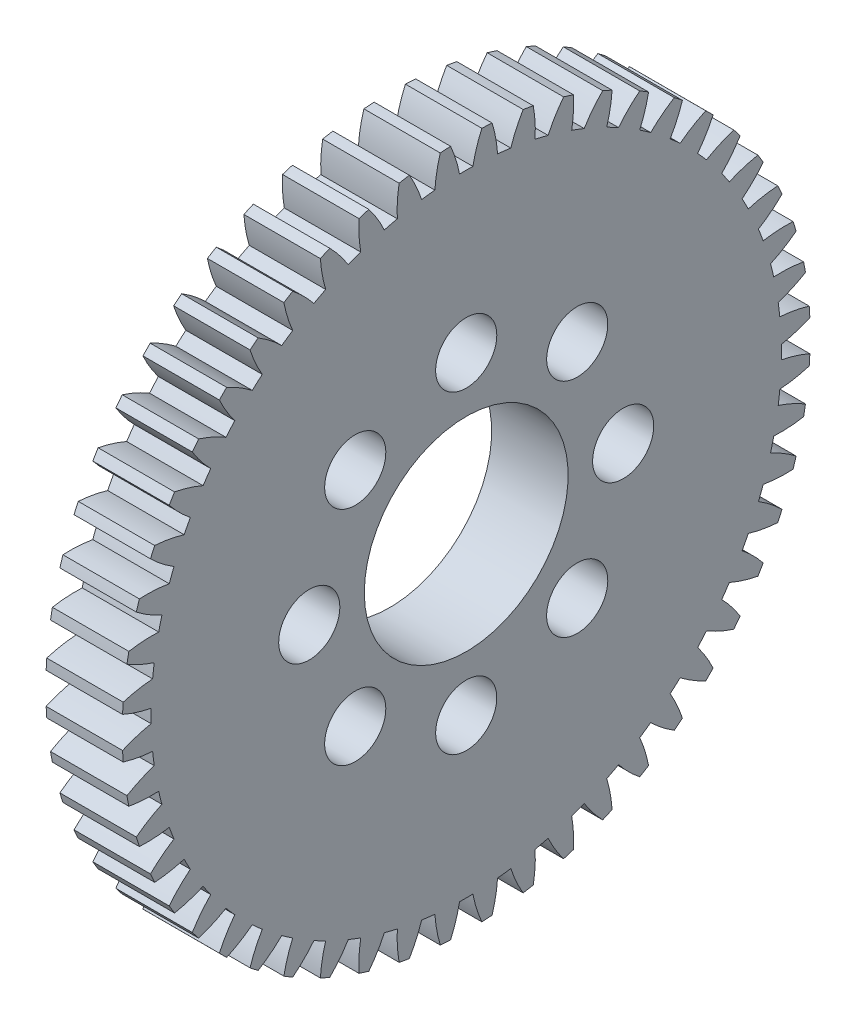
SolidWorks part; units mm, degrees
ref_plane "Front Plane" through (0, 0, 0) normal (0, 0, 1) x (1, 0, 0)
ref_plane "Top Plane" through (0, 0, 0) normal (0, 1, 0) x (1, 0, 0)
ref_plane "Right Plane" through (0, 0, 0) normal (1, 0, 0) x (0, 0, -1)
ref_plane "Plane1" through (-28.2082, 0, 0) normal (1, 0, 0) x (0, 0, -1)
sketch "Sketch1" plane through (-28.2082, 0, 0) normal (1, 0, 0) x (0, 0, -1)
  circle A0 centre (-12.9395, 1.6307) radius 6.35
  arc A1 (-34.3487, 2.6033) -> (-32.5693, 2.0468) centre (-31.0108, 10.1534) ccw
  arc A2 (-32.5693, 2.0468) -> (-32.5693, 1.2146) centre (-12.9395, 1.6307) ccw
  arc A3 (-32.5693, 1.2146) -> (-34.3487, 0.6581) centre (-31.0108, -6.892) ccw
  arc A4 (-34.3487, 0.6581) -> (-34.3098, 0.0156) centre (-12.9395, 1.6307) ccw
  arc A5 (-34.3098, 0.0156) -> (-32.4763, -0.3223) centre (-31.9063, 7.913) ccw
  arc A6 (-32.4763, -0.3223) -> (-32.376, -1.1485) centre (-12.9395, 1.6307) ccw
  arc A7 (-32.376, -1.1485) -> (-34.0753, -1.9154) centre (-29.8517, -9.0081) ccw
  arc A8 (-34.0753, -1.9154) -> (-33.9593, -2.5485) centre (-12.9395, 1.6307) ccw
  arc A9 (-33.9593, -2.5485) -> (-32.0985, -2.663) centre (-32.5252, 5.581) ccw
  arc A10 (-32.0985, -2.663) -> (-31.8993, -3.4711) centre (-12.9395, 1.6307) ccw
  arc A11 (-31.8993, -3.4711) -> (-33.4938, -4.4372) centre (-28.446, -10.9691) ccw
  arc A12 (-33.4938, -4.4372) -> (-33.3023, -5.0517) centre (-12.9395, 1.6307) ccw
  arc A13 (-33.3023, -5.0517) -> (-31.4412, -4.9411) centre (-32.8586, 3.1914) ccw
  arc A14 (-31.4412, -4.9411) -> (-31.1461, -5.7192) centre (-12.9395, 1.6307) ccw
  arc A15 (-31.1461, -5.7192) -> (-32.6125, -6.8705) centre (-26.8142, -12.7463) ccw
  arc A16 (-32.6125, -6.8705) -> (-32.3484, -7.4575) centre (-12.9395, 1.6307) ccw
  arc A17 (-32.3484, -7.4575) -> (-30.5142, -7.1233) centre (-32.9015, 0.779) ccw
  arc A18 (-30.5142, -7.1233) -> (-30.1274, -7.8602) centre (-12.9395, 1.6307) ccw
  arc A19 (-30.1274, -7.8602) -> (-31.4444, -9.1798) centre (-24.9801, -14.3139) ccw
  arc A20 (-31.4444, -9.1798) -> (-31.1114, -9.7307) centre (-12.9395, 1.6307) ccw
  arc A21 (-31.1114, -9.7307) -> (-29.3309, -9.1778) centre (-32.6533, -1.6209) ccw
  arc A22 (-29.3309, -9.1778) -> (-28.8581, -9.8628) centre (-12.9395, 1.6307) ccw
  arc A23 (-28.8581, -9.8628) -> (-30.0064, -11.3315) centre (-22.9704, -15.649) ccw
  arc A24 (-30.0064, -11.3315) -> (-29.6094, -11.8382) centre (-12.9395, 1.6307) ccw
  arc A25 (-29.6094, -11.8382) -> (-27.9085, -11.0748) centre (-32.1176, -3.9735) ccw
  arc A26 (-27.9085, -11.0748) -> (-27.3567, -11.6977) centre (-12.9395, 1.6307) ccw
  arc A27 (-27.3567, -11.6977) -> (-28.3195, -13.2942) centre (-20.8145, -16.7321) ccw
  arc A28 (-28.3195, -13.2942) -> (-27.8644, -13.7493) centre (-12.9395, 1.6307) ccw
  arc A29 (-27.8644, -13.7493) -> (-26.2679, -12.7865) centre (-31.3023, -6.2443) ccw
  arc A30 (-26.2679, -12.7865) -> (-25.645, -13.3384) centre (-12.9395, 1.6307) ccw
  arc A31 (-25.645, -13.3384) -> (-26.4084, -15.0393) centre (-18.5437, -17.5474) ccw
  arc A32 (-26.4084, -15.0393) -> (-25.9017, -15.4362) centre (-12.9395, 1.6307) ccw
  arc A33 (-25.9017, -15.4362) -> (-24.4329, -14.2879) centre (-30.2192, -8.4002) ccw
  arc A34 (-24.4329, -14.2879) -> (-23.748, -14.7607) centre (-12.9395, 1.6307) ccw
  arc A35 (-23.748, -14.7607) -> (-24.3009, -16.5412) centre (-16.1911, -18.0831) ccw
  arc A36 (-24.3009, -16.5412) -> (-23.75, -16.8742) centre (-12.9395, 1.6307) ccw
  arc A37 (-23.75, -16.8742) -> (-22.4304, -15.5572) centre (-28.8841, -10.4099) ccw
  arc A38 (-22.4304, -15.5572) -> (-21.6935, -15.944) centre (-12.9395, 1.6307) ccw
  arc A39 (-21.6935, -15.944) -> (-22.0276, -17.7782) centre (-13.7912, -18.3313) ccw
  arc A40 (-22.0276, -17.7782) -> (-21.4407, -18.0423) centre (-12.9395, 1.6307) ccw
  arc A41 (-21.4407, -18.0423) -> (-20.2894, -16.5759) centre (-27.3165, -12.2441) ccw
  arc A42 (-20.2894, -16.5759) -> (-19.5112, -16.871) centre (-12.9395, 1.6307) ccw
  arc A43 (-19.5112, -16.871) -> (-19.6219, -18.7321) centre (-11.3788, -18.2884) ccw
  arc A44 (-19.6219, -18.7321) -> (-19.0074, -18.9236) centre (-12.9395, 1.6307) ccw
  arc A45 (-19.0074, -18.9236) -> (-18.0412, -17.3291) centre (-25.5392, -13.8758) ccw
  arc A46 (-18.0412, -17.3291) -> (-17.2332, -17.5283) centre (-12.9395, 1.6307) ccw
  arc A47 (-17.2332, -17.5283) -> (-17.1187, -19.3891) centre (-8.9892, -17.9551) ccw
  arc A48 (-17.1187, -19.3891) -> (-16.4856, -19.5051) centre (-12.9395, 1.6307) ccw
  arc A49 (-16.4856, -19.5051) -> (-15.7187, -17.8058) centre (-23.5783, -15.2815) ccw
  arc A50 (-15.7187, -17.8058) -> (-14.8925, -17.9061) centre (-12.9395, 1.6307) ccw
  arc A51 (-14.8925, -17.9061) -> (-14.5546, -19.7396) centre (-6.6572, -17.3361) ccw
  arc A52 (-14.5546, -19.7396) -> (-13.9121, -19.7785) centre (-12.9395, 1.6307) ccw
  arc A53 (-13.9121, -19.7785) -> (-13.3556, -17.9991) centre (-21.4622, -16.4406) ccw
  arc A54 (-13.3556, -17.9991) -> (-12.5234, -17.9991) centre (-12.9395, 1.6307) ccw
  arc A55 (-12.5234, -17.9991) -> (-11.9669, -19.7785) centre (-4.4168, -16.4406) ccw
  arc A56 (-11.9669, -19.7785) -> (-11.3244, -19.7396) centre (-12.9395, 1.6307) ccw
  arc A57 (-11.3244, -19.7396) -> (-10.9865, -17.9061) centre (-19.2218, -17.3361) ccw
  arc A58 (-10.9865, -17.9061) -> (-10.1603, -17.8058) centre (-12.9395, 1.6307) ccw
  arc A59 (-10.1603, -17.8058) -> (-9.3934, -19.5051) centre (-2.3007, -15.2815) ccw
  arc A60 (-9.3934, -19.5051) -> (-8.7603, -19.3891) centre (-12.9395, 1.6307) ccw
  arc A61 (-8.7603, -19.3891) -> (-8.6458, -17.5283) centre (-16.8898, -17.9551) ccw
  arc A62 (-8.6458, -17.5283) -> (-7.8378, -17.3291) centre (-12.9395, 1.6307) ccw
  arc A63 (-7.8378, -17.3291) -> (-6.8716, -18.9236) centre (-0.3397, -13.8758) ccw
  arc A64 (-6.8716, -18.9236) -> (-6.2571, -18.7321) centre (-12.9395, 1.6307) ccw
  arc A65 (-6.2571, -18.7321) -> (-6.3678, -16.871) centre (-14.5002, -18.2884) ccw
  arc A66 (-6.3678, -16.871) -> (-5.5896, -16.5759) centre (-12.9395, 1.6307) ccw
  arc A67 (-5.5896, -16.5759) -> (-4.4383, -18.0423) centre (1.4375, -12.2441) ccw
  arc A68 (-4.4383, -18.0423) -> (-3.8514, -17.7782) centre (-12.9395, 1.6307) ccw
  arc A69 (-3.8514, -17.7782) -> (-4.1855, -15.944) centre (-12.0878, -18.3313) ccw
  arc A70 (-4.1855, -15.944) -> (-3.4486, -15.5572) centre (-12.9395, 1.6307) ccw
  arc A71 (-3.4486, -15.5572) -> (-2.129, -16.8742) centre (3.0051, -10.4099) ccw
  arc A72 (-2.129, -16.8742) -> (-1.5781, -16.5412) centre (-12.9395, 1.6307) ccw
  arc A73 (-1.5781, -16.5412) -> (-2.131, -14.7607) centre (-9.6879, -18.0831) ccw
  arc A74 (-2.131, -14.7607) -> (-1.446, -14.2879) centre (-12.9395, 1.6307) ccw
  arc A75 (-1.446, -14.2879) -> (0.0227, -15.4362) centre (4.3402, -8.4002) ccw
  arc A76 (0.0227, -15.4362) -> (0.5294, -15.0393) centre (-12.9395, 1.6307) ccw
  arc A77 (0.5294, -15.0393) -> (-0.234, -13.3384) centre (-7.3353, -17.5474) ccw
  arc A78 (-0.234, -13.3384) -> (0.3889, -12.7865) centre (-12.9395, 1.6307) ccw
  arc A79 (0.3889, -12.7865) -> (1.9854, -13.7493) centre (5.4233, -6.2443) ccw
  arc A80 (1.9854, -13.7493) -> (2.4405, -13.2942) centre (-12.9395, 1.6307) ccw
  arc A81 (2.4405, -13.2942) -> (1.4777, -11.6977) centre (-5.0645, -16.7321) ccw
  arc A82 (1.4777, -11.6977) -> (2.0296, -11.0748) centre (-12.9395, 1.6307) ccw
  arc A83 (2.0296, -11.0748) -> (3.7305, -11.8382) centre (6.2386, -3.9735) ccw
  arc A84 (3.7305, -11.8382) -> (4.1274, -11.3315) centre (-12.9395, 1.6307) ccw
  arc A85 (4.1274, -11.3315) -> (2.9791, -9.8628) centre (-2.9086, -15.649) ccw
  arc A86 (2.9791, -9.8628) -> (3.4519, -9.1778) centre (-12.9395, 1.6307) ccw
  arc A87 (3.4519, -9.1778) -> (5.2324, -9.7307) centre (6.7743, -1.6209) ccw
  arc A88 (5.2324, -9.7307) -> (5.5654, -9.1798) centre (-12.9395, 1.6307) ccw
  arc A89 (5.5654, -9.1798) -> (4.2484, -7.8602) centre (-0.8989, -14.3139) ccw
  arc A90 (4.2484, -7.8602) -> (4.6352, -7.1233) centre (-12.9395, 1.6307) ccw
  arc A91 (4.6352, -7.1233) -> (6.4694, -7.4575) centre (7.0225, 0.779) ccw
  arc A92 (6.4694, -7.4575) -> (6.7335, -6.8705) centre (-12.9395, 1.6307) ccw
  arc A93 (6.7335, -6.8705) -> (5.2671, -5.7192) centre (0.9353, -12.7463) ccw
  arc A94 (5.2671, -5.7192) -> (5.5622, -4.9411) centre (-12.9395, 1.6307) ccw
  arc A95 (5.5622, -4.9411) -> (7.4233, -5.0517) centre (6.9796, 3.1914) ccw
  arc A96 (7.4233, -5.0517) -> (7.6148, -4.4372) centre (-12.9395, 1.6307) ccw
  arc A97 (7.6148, -4.4372) -> (6.0203, -3.4711) centre (2.567, -10.9691) ccw
  arc A98 (6.0203, -3.4711) -> (6.2195, -2.663) centre (-12.9395, 1.6307) ccw
  arc A99 (6.2195, -2.663) -> (8.0803, -2.5485) centre (6.6463, 5.581) ccw
  arc A100 (8.0803, -2.5485) -> (8.1963, -1.9154) centre (-12.9395, 1.6307) ccw
  arc A101 (8.1963, -1.9154) -> (6.497, -1.1485) centre (3.9727, -9.0081) ccw
  arc A102 (6.497, -1.1485) -> (6.5973, -0.3223) centre (-12.9395, 1.6307) ccw
  arc A103 (6.5973, -0.3223) -> (8.4308, 0.0156) centre (6.0273, 7.913) ccw
  arc A104 (8.4308, 0.0156) -> (8.4697, 0.6581) centre (-12.9395, 1.6307) ccw
  arc A105 (8.4697, 0.6581) -> (6.6903, 1.2146) centre (5.1318, -6.892) ccw
  arc A106 (6.6903, 1.2146) -> (6.6903, 2.0468) centre (-12.9395, 1.6307) ccw
  arc A107 (6.6903, 2.0468) -> (8.4697, 2.6033) centre (5.1318, 10.1534) ccw
  arc A108 (8.4697, 2.6033) -> (8.4308, 3.2458) centre (-12.9395, 1.6307) ccw
  arc A109 (8.4308, 3.2458) -> (6.5973, 3.5837) centre (6.0273, -4.6516) ccw
  arc A110 (6.5973, 3.5837) -> (6.497, 4.4099) centre (-12.9395, 1.6307) ccw
  arc A111 (6.497, 4.4099) -> (8.1963, 5.1768) centre (3.9727, 12.2695) ccw
  arc A112 (8.1963, 5.1768) -> (8.0803, 5.8099) centre (-12.9395, 1.6307) ccw
  arc A113 (8.0803, 5.8099) -> (6.2195, 5.9244) centre (6.6463, -2.3196) ccw
  arc A114 (6.2195, 5.9244) -> (6.0203, 6.7324) centre (-12.9395, 1.6307) ccw
  arc A115 (6.0203, 6.7324) -> (7.6148, 7.6986) centre (2.567, 14.2304) ccw
  arc A116 (7.6148, 7.6986) -> (7.4233, 8.3131) centre (-12.9395, 1.6307) ccw
  arc A117 (7.4233, 8.3131) -> (5.5622, 8.2024) centre (6.9796, 0.07) ccw
  arc A118 (5.5622, 8.2024) -> (5.2671, 8.9806) centre (-12.9395, 1.6307) ccw
  arc A119 (5.2671, 8.9806) -> (6.7335, 10.1319) centre (0.9353, 16.0077) ccw
  arc A120 (6.7335, 10.1319) -> (6.4694, 10.7188) centre (-12.9395, 1.6307) ccw
  arc A121 (6.4694, 10.7188) -> (4.6352, 10.3847) centre (7.0225, 2.4824) ccw
  arc A122 (4.6352, 10.3847) -> (4.2484, 11.1216) centre (-12.9395, 1.6307) ccw
  arc A123 (4.2484, 11.1216) -> (5.5654, 12.4412) centre (-0.8989, 17.5753) ccw
  arc A124 (5.5654, 12.4412) -> (5.2324, 12.992) centre (-12.9395, 1.6307) ccw
  arc A125 (5.2324, 12.992) -> (3.4519, 12.4392) centre (6.7743, 4.8823) ccw
  arc A126 (3.4519, 12.4392) -> (2.9791, 13.1241) centre (-12.9395, 1.6307) ccw
  arc A127 (2.9791, 13.1241) -> (4.1274, 14.5929) centre (-2.9086, 18.9103) ccw
  arc A128 (4.1274, 14.5929) -> (3.7305, 15.0996) centre (-12.9395, 1.6307) ccw
  arc A129 (3.7305, 15.0996) -> (2.0296, 14.3362) centre (6.2386, 7.2349) ccw
  arc A130 (2.0296, 14.3362) -> (1.4777, 14.9591) centre (-12.9395, 1.6307) ccw
  arc A131 (1.4777, 14.9591) -> (2.4405, 16.5556) centre (-5.0645, 19.9935) ccw
  arc A132 (2.4405, 16.5556) -> (1.9854, 17.0107) centre (-12.9395, 1.6307) ccw
  arc A133 (1.9854, 17.0107) -> (0.3889, 16.0479) centre (5.4233, 9.5057) ccw
  arc A134 (0.3889, 16.0479) -> (-0.234, 16.5997) centre (-12.9395, 1.6307) ccw
  arc A135 (-0.234, 16.5997) -> (0.5294, 18.3006) centre (-7.3353, 20.8088) ccw
  arc A136 (0.5294, 18.3006) -> (0.0227, 18.6976) centre (-12.9395, 1.6307) ccw
  arc A137 (0.0227, 18.6976) -> (-1.446, 17.5493) centre (4.3402, 11.6616) ccw
  arc A138 (-1.446, 17.5493) -> (-2.131, 18.0221) centre (-12.9395, 1.6307) ccw
  arc A139 (-2.131, 18.0221) -> (-1.5781, 19.8026) centre (-9.6879, 21.3445) ccw
  arc A140 (-1.5781, 19.8026) -> (-2.129, 20.1356) centre (-12.9395, 1.6307) ccw
  arc A141 (-2.129, 20.1356) -> (-3.4486, 18.8186) centre (3.0051, 13.6713) ccw
  arc A142 (-3.4486, 18.8186) -> (-4.1855, 19.2054) centre (-12.9395, 1.6307) ccw
  arc A143 (-4.1855, 19.2054) -> (-3.8514, 21.0396) centre (-12.0878, 21.5927) ccw
  arc A144 (-3.8514, 21.0396) -> (-4.4383, 21.3037) centre (-12.9395, 1.6307) ccw
  arc A145 (-4.4383, 21.3037) -> (-5.5896, 19.8373) centre (1.4375, 15.5054) ccw
  arc A146 (-5.5896, 19.8373) -> (-6.3678, 20.1324) centre (-12.9395, 1.6307) ccw
  arc A147 (-6.3678, 20.1324) -> (-6.2571, 21.9935) centre (-14.5002, 21.5498) ccw
  arc A148 (-6.2571, 21.9935) -> (-6.8716, 22.185) centre (-12.9395, 1.6307) ccw
  arc A149 (-6.8716, 22.185) -> (-7.8378, 20.5905) centre (-0.3397, 17.1372) ccw
  arc A150 (-7.8378, 20.5905) -> (-8.6458, 20.7897) centre (-12.9395, 1.6307) ccw
  arc A151 (-8.6458, 20.7897) -> (-8.7603, 22.6505) centre (-16.8898, 21.2164) ccw
  arc A152 (-8.7603, 22.6505) -> (-9.3934, 22.7665) centre (-12.9395, 1.6307) ccw
  arc A153 (-9.3934, 22.7665) -> (-10.1603, 21.0672) centre (-2.3007, 18.5429) ccw
  arc A154 (-10.1603, 21.0672) -> (-10.9865, 21.1675) centre (-12.9395, 1.6307) ccw
  arc A155 (-10.9865, 21.1675) -> (-11.3244, 23.001) centre (-19.2218, 20.5975) ccw
  arc A156 (-11.3244, 23.001) -> (-11.9669, 23.0399) centre (-12.9395, 1.6307) ccw
  arc A157 (-11.9669, 23.0399) -> (-12.5234, 21.2605) centre (-4.4168, 19.702) ccw
  arc A158 (-12.5234, 21.2605) -> (-13.3556, 21.2605) centre (-12.9395, 1.6307) ccw
  arc A159 (-13.3556, 21.2605) -> (-13.9121, 23.0399) centre (-21.4622, 19.702) ccw
  arc A160 (-13.9121, 23.0399) -> (-14.5546, 23.001) centre (-12.9395, 1.6307) ccw
  arc A161 (-14.5546, 23.001) -> (-14.8925, 21.1675) centre (-6.6572, 20.5975) ccw
  arc A162 (-14.8925, 21.1675) -> (-15.7187, 21.0672) centre (-12.9395, 1.6307) ccw
  arc A163 (-15.7187, 21.0672) -> (-16.4856, 22.7665) centre (-23.5783, 18.5429) ccw
  arc A164 (-16.4856, 22.7665) -> (-17.1187, 22.6505) centre (-12.9395, 1.6307) ccw
  arc A165 (-17.1187, 22.6505) -> (-17.2332, 20.7897) centre (-8.9892, 21.2164) ccw
  arc A166 (-17.2332, 20.7897) -> (-18.0412, 20.5905) centre (-12.9395, 1.6307) ccw
  arc A167 (-18.0412, 20.5905) -> (-19.0074, 22.185) centre (-25.5392, 17.1372) ccw
  arc A168 (-19.0074, 22.185) -> (-19.6219, 21.9935) centre (-12.9395, 1.6307) ccw
  arc A169 (-19.6219, 21.9935) -> (-19.5112, 20.1324) centre (-11.3788, 21.5498) ccw
  arc A170 (-19.5112, 20.1324) -> (-20.2894, 19.8373) centre (-12.9395, 1.6307) ccw
  arc A171 (-20.2894, 19.8373) -> (-21.4407, 21.3037) centre (-27.3165, 15.5054) ccw
  arc A172 (-21.4407, 21.3037) -> (-22.0276, 21.0396) centre (-12.9395, 1.6307) ccw
  arc A173 (-22.0276, 21.0396) -> (-21.6935, 19.2054) centre (-13.7912, 21.5927) ccw
  arc A174 (-21.6935, 19.2054) -> (-22.4304, 18.8186) centre (-12.9395, 1.6307) ccw
  arc A175 (-22.4304, 18.8186) -> (-23.75, 20.1356) centre (-28.8841, 13.6713) ccw
  arc A176 (-23.75, 20.1356) -> (-24.3009, 19.8026) centre (-12.9395, 1.6307) ccw
  arc A177 (-24.3009, 19.8026) -> (-23.748, 18.0221) centre (-16.1911, 21.3445) ccw
  arc A178 (-23.748, 18.0221) -> (-24.4329, 17.5493) centre (-12.9395, 1.6307) ccw
  arc A179 (-24.4329, 17.5493) -> (-25.9017, 18.6976) centre (-30.2192, 11.6616) ccw
  arc A180 (-25.9017, 18.6976) -> (-26.4084, 18.3006) centre (-12.9395, 1.6307) ccw
  arc A181 (-26.4084, 18.3006) -> (-25.645, 16.5997) centre (-18.5437, 20.8088) ccw
  arc A182 (-25.645, 16.5997) -> (-26.2679, 16.0479) centre (-12.9395, 1.6307) ccw
  arc A183 (-26.2679, 16.0479) -> (-27.8644, 17.0107) centre (-31.3023, 9.5057) ccw
  arc A184 (-27.8644, 17.0107) -> (-28.3195, 16.5556) centre (-12.9395, 1.6307) ccw
  arc A185 (-28.3195, 16.5556) -> (-27.3567, 14.9591) centre (-20.8145, 19.9935) ccw
  arc A186 (-27.3567, 14.9591) -> (-27.9085, 14.3362) centre (-12.9395, 1.6307) ccw
  arc A187 (-27.9085, 14.3362) -> (-29.6094, 15.0996) centre (-32.1176, 7.2349) ccw
  arc A188 (-29.6094, 15.0996) -> (-30.0064, 14.5929) centre (-12.9395, 1.6307) ccw
  arc A189 (-30.0064, 14.5929) -> (-28.8581, 13.1241) centre (-22.9704, 18.9103) ccw
  arc A190 (-28.8581, 13.1241) -> (-29.3309, 12.4392) centre (-12.9395, 1.6307) ccw
  arc A191 (-29.3309, 12.4392) -> (-31.1114, 12.992) centre (-32.6533, 4.8823) ccw
  arc A192 (-31.1114, 12.992) -> (-31.4444, 12.4412) centre (-12.9395, 1.6307) ccw
  arc A193 (-31.4444, 12.4412) -> (-30.1274, 11.1216) centre (-24.9801, 17.5753) ccw
  arc A194 (-30.1274, 11.1216) -> (-30.5142, 10.3847) centre (-12.9395, 1.6307) ccw
  arc A195 (-30.5142, 10.3847) -> (-32.3484, 10.7188) centre (-32.9015, 2.4824) ccw
  arc A196 (-32.3484, 10.7188) -> (-32.6125, 10.1319) centre (-12.9395, 1.6307) ccw
  arc A197 (-32.6125, 10.1319) -> (-31.1461, 8.9806) centre (-26.8142, 16.0077) ccw
  arc A198 (-31.1461, 8.9806) -> (-31.4412, 8.2024) centre (-12.9395, 1.6307) ccw
  arc A199 (-31.4412, 8.2024) -> (-33.3023, 8.3131) centre (-32.8586, 0.07) ccw
  arc A200 (-33.3023, 8.3131) -> (-33.4938, 7.6986) centre (-12.9395, 1.6307) ccw
  arc A201 (-33.4938, 7.6986) -> (-31.8993, 6.7324) centre (-28.446, 14.2304) ccw
  arc A202 (-31.8993, 6.7324) -> (-32.0985, 5.9244) centre (-12.9395, 1.6307) ccw
  arc A203 (-32.0985, 5.9244) -> (-33.9593, 5.8099) centre (-32.5252, -2.3196) ccw
  arc A204 (-33.9593, 5.8099) -> (-34.0753, 5.1768) centre (-12.9395, 1.6307) ccw
  arc A205 (-34.0753, 5.1768) -> (-32.376, 4.4099) centre (-29.8517, 12.2695) ccw
  arc A206 (-32.376, 4.4099) -> (-32.4763, 3.5837) centre (-12.9395, 1.6307) ccw
  arc A207 (-32.4763, 3.5837) -> (-34.3098, 3.2458) centre (-31.9063, -4.6516) ccw
  arc A208 (-34.3098, 3.2458) -> (-34.3487, 2.6033) centre (-12.9395, 1.6307) ccw
extrude "Boss-Extrude1" add sketch "Sketch1" against normal blind 4.7625
sketch "Sketch2" plane through (-28.2082, 0, 0) normal (1, 0, 0) x (0, 0, -1)
  circle A2 centre (-12.9395, 11.4097) radius 1.905
  point P14 (-12.9395, 1.6307)
  point P17 (-12.9395, 1.6307)
  dimension "D1" = 9.779
  dimension "D2" = 3.81
extrude "Cut-Extrude1" cut sketch "Sketch2" against normal through all
pattern_circular "CirPattern1" count 8 over 360 about axis through (0, 1.6307, 12.9395) along (1, 0, 0) of "Cut-Extrude1"
